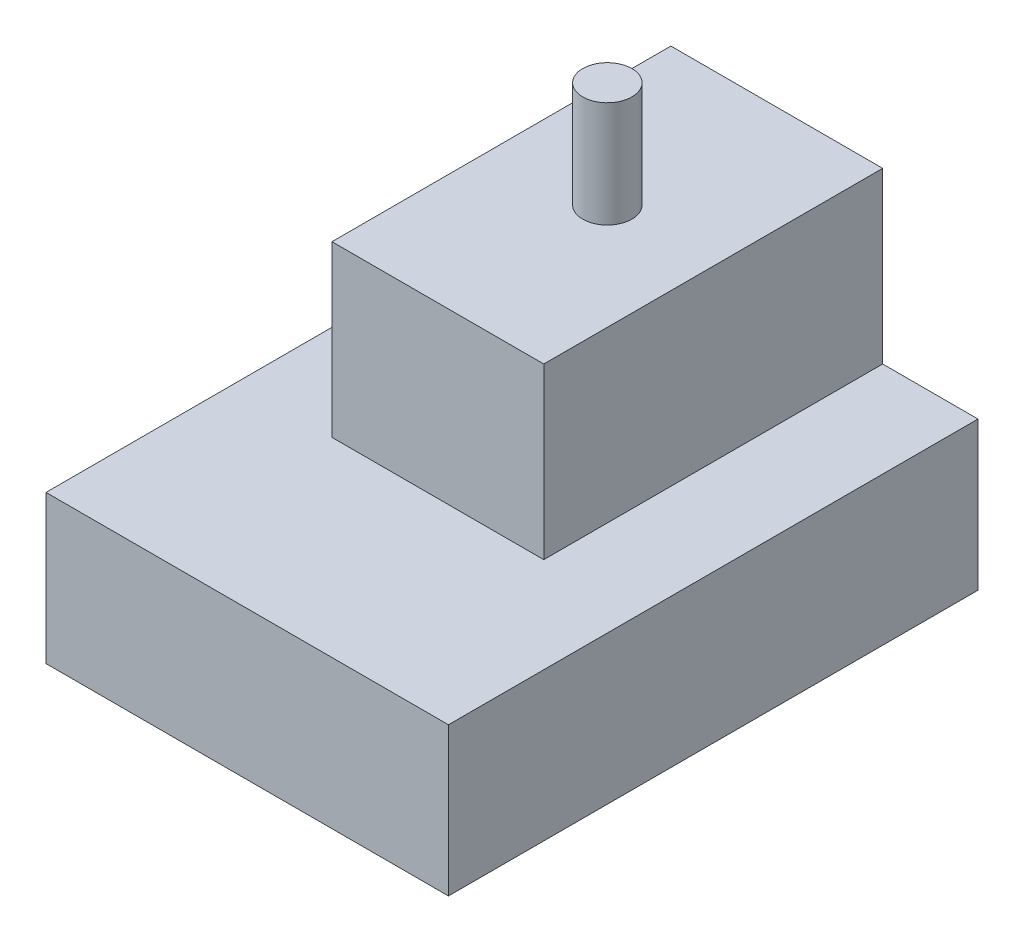
SolidWorks part; units mm, degrees
material "ABS PC"
ref_plane "Front Plane" through (0, 0, 0) normal (0, 0, 1) x (1, 0, 0)
ref_plane "Top Plane" through (0, 0, 0) normal (0, 1, 0) x (1, 0, 0)
ref_plane "Right Plane" through (0, 0, 0) normal (1, 0, 0) x (0, 0, -1)
sketch "Sketch1" plane through (0, 0, 0) normal (0, 0, 1) x (1, 0, 0)
  line L1 (-6.0325, -4.7625) -> (6.0325, -4.7625)
  line L2 (-6.0325, -4.7625) -> (-6.0325, 4.7625)
  line L3 (-6.0325, 4.7625) -> (6.0325, 4.7625)
  line L4 (6.0325, -4.7625) -> (6.0325, 4.7625)
  line L5 (-6.0325, -4.7625) -> (6.0325, 4.7625) construction
  line L6 (-6.0325, 4.7625) -> (6.0325, -4.7625) construction
  point P0 (0, 0)
  dimension "D1" = 12.065
  dimension "D2" = 9.525
extrude "Base" add sketch "Sketch1" along normal blind 15.875
sketch "Sketch3" plane through (0, 0, 0) normal (0, 0, -1) x (-1, 0, 0)
  line L0 (6.0325, -4.7625) -> (-6.0325, -4.7625) construction
  circle A0 centre (0, 6.3627) radius 1.397
  dimension "D1" = 2.794
  dimension "D2" = 11.1252
extrude "ShaftHole" [suppressed] cut sketch "Sketch3" against normal through all
sketch "Sketch7" plane through (0, 4.7625, 0) normal (0, 1, 0) x (1, 0, 0)
  line L1 (-3.175, -10.16) -> (3.175, -10.16)
  line L2 (-3.175, -10.16) -> (-3.175, 0)
  line L3 (-3.175, 0) -> (3.175, 0)
  line L4 (3.175, -10.16) -> (3.175, 0)
  line L5 (-8.4027, 3.7179) -> (9.7417, 3.7179)
  line L6 (-8.4027, 3.7179) -> (-8.4027, -18.9497)
  line L7 (-8.4027, -18.9497) -> (9.7417, -18.9497)
  line L8 (9.7417, 3.7179) -> (9.7417, -18.9497)
  line L15 (6.0325, 0) -> (-6.0325, 0) construction
  dimension "D1" = 6.35
  dimension "D2" = 10.16
extrude "Cut-Extrude1" cut sketch "Sketch7" against normal blind 5.08
sketch "Sketch8" plane through (0, 4.7625, 0) normal (0, 1, 0) x (1, 0, 0)
  line L0 (3.175, 0) -> (-3.175, 0) construction
  circle A0 centre (0, -5.08) radius 0.7366
  dimension "D1" = 1.4732
  dimension "D2" = 5.08
extrude "Boss-Extrude1" add sketch "Sketch8" along normal blind 3.175 separate body
